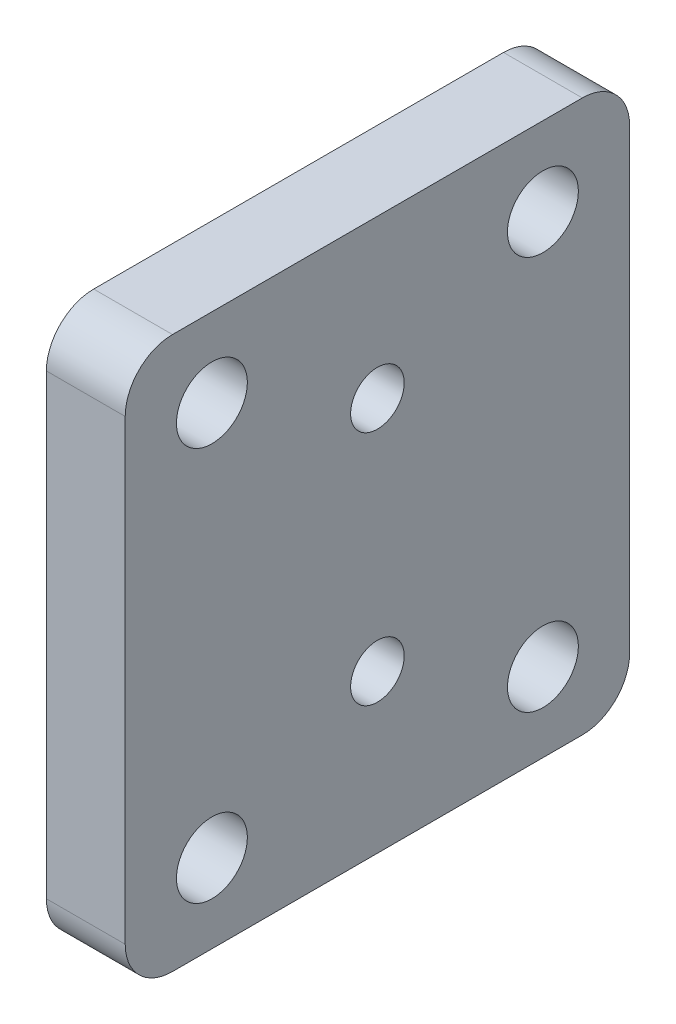
SolidWorks part; units mm, degrees
ref_plane "前视基准面" through (0, 0, 0) normal (0, 0, 1) x (1, 0, 0)
ref_plane "上视基准面" through (0, 0, 0) normal (0, 1, 0) x (1, 0, 0)
ref_plane "右视基准面" through (0, 0, 0) normal (1, 0, 0) x (0, 0, -1)
other "Configuration Table"
sketch "草图1" plane through (0, 0, 0) normal (1, 0, 0) x (0, 0, -1)
  line L1 (0, 0) -> (32, 0)
  line L2 (0, 0) -> (0, 35)
  line L3 (0, 35) -> (32, 35)
  line L4 (32, 0) -> (32, 35)
  circle A0 centre (5.5, 30) radius 2.25
  circle A1 centre (26.5, 30) radius 2.25
  circle A2 centre (5.5, 5) radius 2.25
  circle A3 centre (26.5, 5) radius 2.25
  circle A4 centre (16, 25) radius 3
  circle A5 centre (16, 10) radius 3
  dimension "D3" = 5
  dimension "D5" = 21
  dimension "D6" = 4.5
  dimension "D7" = 4.5
  dimension "D8" = 4.5
  dimension "D9" = 25
  dimension "D10" = 25
  dimension "D11" = 21
  dimension "D12" = 6
  dimension "D14" = 10
  dimension "D15" = 10
  dimension "D1" = 32
  dimension "D2" = 35
  dimension "D4" = 5.5
  dimension "D13" = 16
extrude "凸台-拉伸1" add sketch "草图1" along normal blind 2.5
sketch "草图2" plane through (2.5, 0, 0) normal (1, 0, 0) x (0, 0, -1)
  line L0 (0, 0) -> (32, 0) construction
  line L1 (32, 0) -> (32, 35) construction
  line L2 (0, 35) -> (0, 0) construction
  line L3 (32, 35) -> (0, 35) construction
  line L4 (0, 0) -> (32, 0)
  line L5 (32, 0) -> (32, 35)
  line L6 (0, 35) -> (0, 0)
  line L7 (32, 35) -> (0, 35)
  circle A0 centre (26.5, 5) radius 2.25 construction
  circle A1 centre (5.5, 5) radius 2.25 construction
  circle A2 centre (26.5, 30) radius 2.25 construction
  circle A3 centre (5.5, 30) radius 2.25 construction
  circle A4 centre (26.5, 5) radius 2.25
  circle A5 centre (5.5, 5) radius 2.25
  circle A6 centre (26.5, 30) radius 2.25
  circle A7 centre (5.5, 30) radius 2.25
  circle A9 centre (16, 25) radius 1.7
  circle A10 centre (16, 10) radius 1.7
extrude "凸台-拉伸2" add sketch "草图2" along normal blind 2.5
fillet "圆角1" radius 3 4 edges at (2.5, 35, -32) (2.5, 0, -32) (2.5, 0, 0) (2.5, 35, 0)
